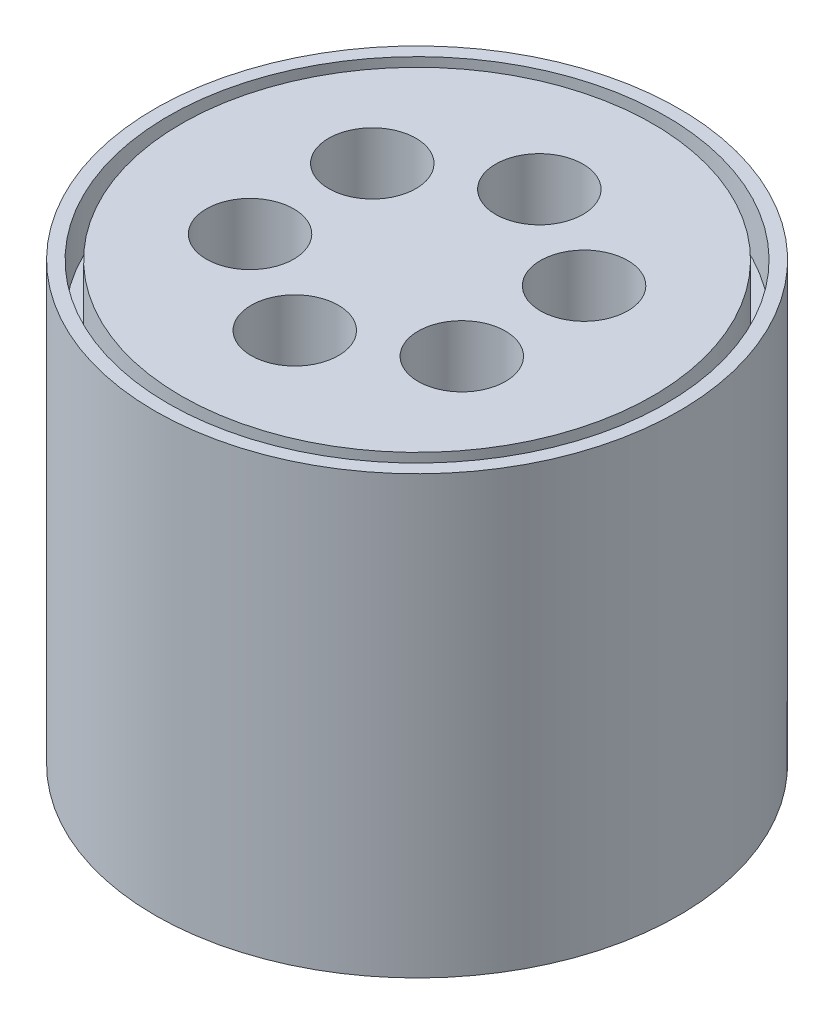
SolidWorks part; units mm, degrees
material "6061-T6 (SS)"
ref_plane "Front Plane" through (0, 0, 0) normal (0, 0, 1) x (1, 0, 0)
ref_plane "Top Plane" through (0, 0, 0) normal (0, 1, 0) x (1, 0, 0)
ref_plane "Right Plane" through (0, 0, 0) normal (1, 0, 0) x (0, 0, -1)
sketch "Sketch1" plane through (0, 0, 0) normal (0, 1, 0) x (1, 0, 0)
  circle A0 centre (0, 0) radius 15
  dimension "D1" = 30
extrude "Boss-Extrude1" add sketch "Sketch1" along normal blind 25
sketch "Sketch4" plane through (0, 25, 0) normal (0, 1, 0) x (1, 0, 0)
  circle A0 centre (0, 0) radius 13.5
  circle A1 centre (0, 0) radius 14.25
  dimension "D1" = 28.5
  dimension "D2" = 27
extrude "Cut-Extrude2" cut sketch "Sketch4" against normal blind 3
sketch "Sketch5" plane through (0, 25, 0) normal (0, 1, 0) x (1, 0, 0)
  circle A0 centre (0, 0) radius 7 construction
  circle A1 centre (0, 7) radius 2.5
  circle A2 centre (6.0622, 3.5) radius 2.5
  circle A3 centre (6.0622, -3.5) radius 2.5
  circle A4 centre (0, -7) radius 2.5
  circle A5 centre (-6.0622, -3.5) radius 2.5
  circle A6 centre (-6.0622, 3.5) radius 2.5
  point P18 (0, 0)
  dimension "D1" = 5
  dimension "D2" = 14
  dimension "D3" = 6
extrude "Cut-Extrude3" cut sketch "Sketch5" against normal blind 22
sketch "Sketch6" plane through (0, 0, 0) normal (0, -1, 0) x (1, 0, 0)
  circle A0 centre (0, 0) radius 2.5
  dimension "D1" = 5
extrude "Cut-Extrude4" cut sketch "Sketch6" against normal blind 10
